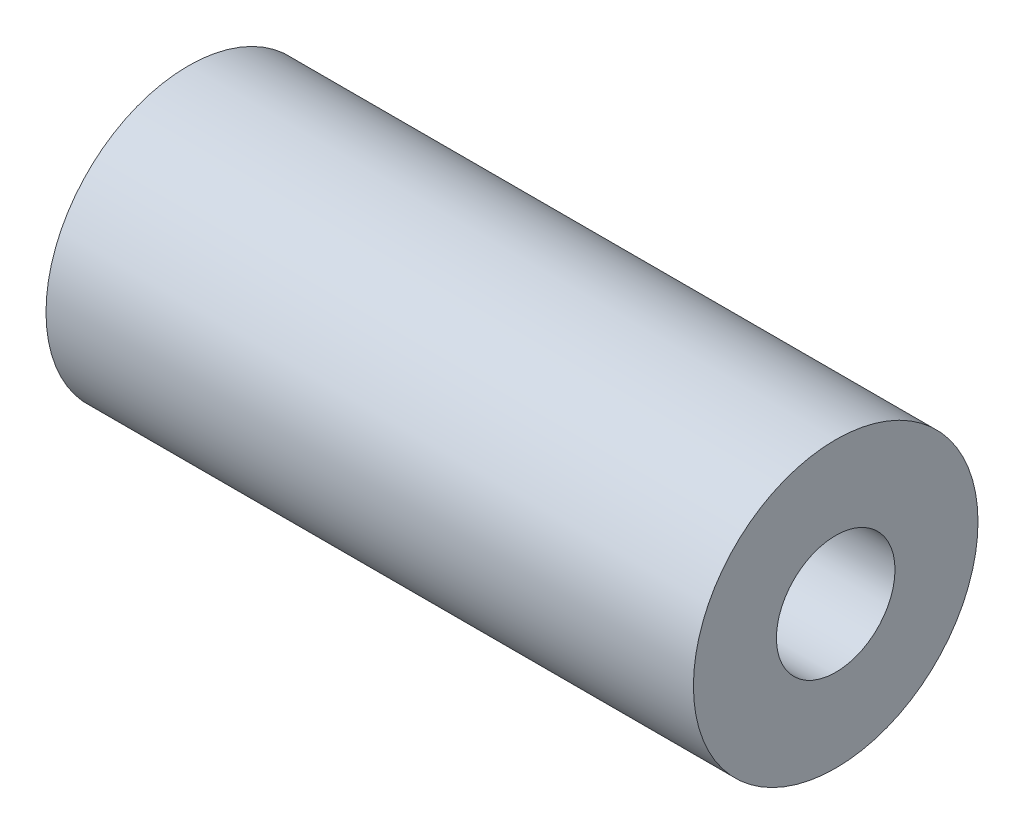
SolidWorks part; units mm, degrees
material "6061-T6 (SS)"
ref_plane "Front Plane" through (0, 0, 0) normal (1, 0, 0) x (0, 1, 0)
ref_plane "Top Plane" through (0, 0, 0) normal (0, 0, 1) x (0, 1, 0)
ref_plane "Right Plane" through (0, 0, 0) normal (0, 1, 0) x (-1, 0, 0)
sketch "Sketch1" plane through (0, 0, 0) normal (1, 0, 0) x (0, 1, 0)
  circle A0 centre (0, 0) radius 3
  dimension "D1" = 6
extrude "Boss-Extrude1" add sketch "Sketch1" along normal blind 13.65
hole_wizard "Tap Drill for M3x0.5 Tap1" positions "Sketch2" profile "Sketch3" hole size "M3x0.5" standard "ANSI Metric" end condition through all
sketch "Sketch2" plane through (13.65, 0, 0) normal (1, 0, 0) x (0, 0, -1)
  point P0 (0, 0)
sketch "Sketch3" plane through (13.65, 0, 0) normal (0, 1, 0) x (0, 0, -1)
  line L0 (0, 0) -> (0, 13.65)
  line L1 (0, 13.65) -> (1.25, 13.65)
  line L2 (1.25, 13.65) -> (1.25, 0)
  line L5 (1.25, 0) -> (0, 0)
  line L11 (0, -6.35) -> (0, 107.95) construction
  dimension "Thru Hole Dia." = 2.5
  dimension "Thru Hole Depth" = 13.65
